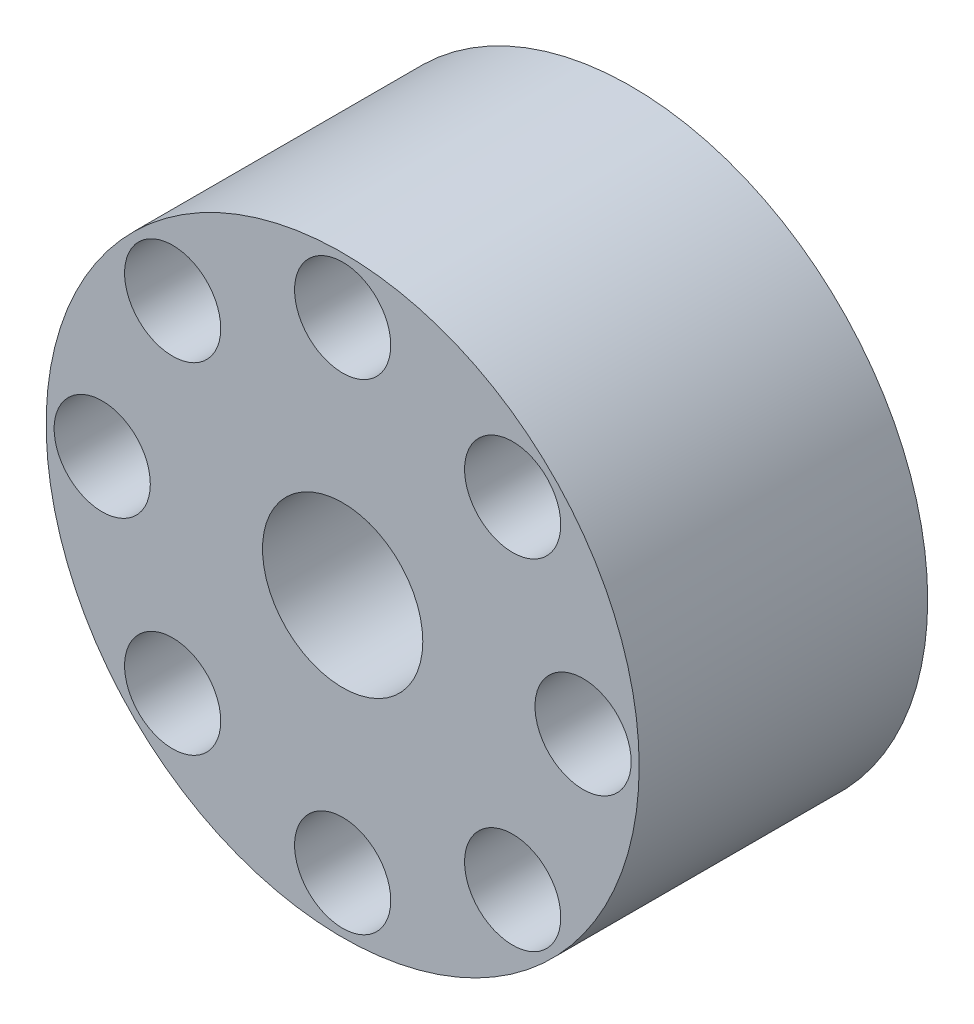
SolidWorks part; units mm, degrees
ref_plane "前视基准面" through (0, 0, 0) normal (0, 0, 1) x (1, 0, 0)
ref_plane "上视基准面" through (0, 0, 0) normal (0, 1, 0) x (1, 0, 0)
ref_plane "右视基准面" through (0, 0, 0) normal (1, 0, 0) x (0, 0, -1)
sketch "草图1" plane through (0, 0, 0) normal (0, 0, 1) x (1, 0, 0)
  circle A0 centre (0, 0) radius 18.5
  circle A1 centre (15, 0) radius 3
  circle A2 centre (10.6066, -10.6066) radius 3
  circle A3 centre (0, -15) radius 3
  circle A4 centre (-10.6066, -10.6066) radius 3
  circle A5 centre (-15, 0) radius 3
  circle A6 centre (-10.6066, 10.6066) radius 3
  circle A7 centre (0, 15) radius 3
  circle A8 centre (10.6066, 10.6066) radius 3
  circle A9 centre (0, 0) radius 5
  dimension "D1" = 37
  dimension "D2" = 6
  dimension "D5" = 10
  dimension "D3" = 15
  dimension "D4" = 8
extrude "凸台-拉伸1" add sketch "草图1" along normal blind 18
